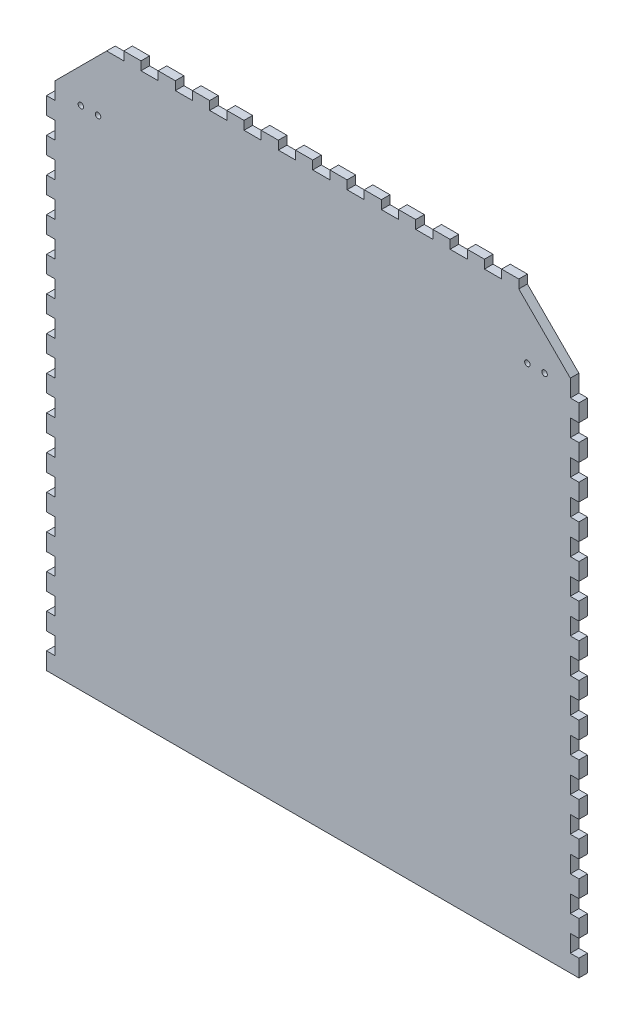
SolidWorks part; units mm, degrees
material "Buche"
ref_plane "Ebene vorne" through (0, 0, 0) normal (0, 0, 1) x (1, 0, 0)
ref_plane "Ebene oben" through (0, 0, 0) normal (0, 1, 0) x (1, 0, 0)
ref_plane "Ebene rechts" through (0, 0, 0) normal (1, 0, 0) x (0, 0, -1)
sketch "Skizze1" plane through (0, 0, 0) normal (0, 0, 1) x (1, 0, 0)
  line L0 (5, 10) -> (5, 20)
  line L1 (5, -10) -> (5, 0)
  line L2 (305, 10) -> (305, 20)
  line L3 (55, 250) -> (65, 250)
  line L4 (5, 220) -> (35, 250)
  line L5 (305, 220) -> (275, 250)
  line L6 (35, 250) -> (45, 250)
  line L7 (45, 250) -> (45, 255)
  line L8 (45, 255) -> (55, 255)
  line L9 (55, 255) -> (55, 250)
  line L10 (65, 250) -> (65, 255)
  line L11 (65, 255) -> (75, 255)
  line L12 (75, 255) -> (75, 250)
  line L13 (305, 0) -> (310, 0)
  line L14 (310, 0) -> (310, 10)
  line L15 (310, 10) -> (305, 10)
  line L16 (305, 30) -> (305, 40)
  line L17 (305, 20) -> (310, 20)
  line L18 (310, 20) -> (310, 30)
  line L19 (310, 30) -> (305, 30)
  line L20 (305, 50) -> (305, 60)
  line L21 (305, 40) -> (310, 40)
  line L22 (310, 40) -> (310, 50)
  line L23 (310, 50) -> (305, 50)
  line L24 (305, 70) -> (305, 80)
  line L25 (305, 60) -> (310, 60)
  line L26 (310, 60) -> (310, 70)
  line L27 (310, 70) -> (305, 70)
  line L28 (305, 90) -> (305, 100)
  line L29 (305, 80) -> (310, 80)
  line L30 (310, 80) -> (310, 90)
  line L31 (310, 90) -> (305, 90)
  line L32 (305, 110) -> (305, 120)
  line L33 (305, 100) -> (310, 100)
  line L34 (310, 100) -> (310, 110)
  line L35 (310, 110) -> (305, 110)
  line L36 (305, 130) -> (305, 140)
  line L37 (305, 120) -> (310, 120)
  line L38 (310, 120) -> (310, 130)
  line L39 (310, 130) -> (305, 130)
  line L40 (305, 150) -> (305, 160)
  line L41 (305, 140) -> (310, 140)
  line L42 (310, 140) -> (310, 150)
  line L43 (310, 150) -> (305, 150)
  line L44 (305, 170) -> (305, 180)
  line L45 (305, 160) -> (310, 160)
  line L46 (310, 160) -> (310, 170)
  line L47 (310, 170) -> (305, 170)
  line L48 (305, 190) -> (305, 200)
  line L49 (305, 180) -> (310, 180)
  line L50 (310, 180) -> (310, 190)
  line L51 (310, 190) -> (305, 190)
  line L52 (305, 210) -> (305, 220)
  line L53 (305, 200) -> (310, 200)
  line L54 (310, 200) -> (310, 210)
  line L55 (310, 210) -> (305, 210)
  line L56 (5, 0) -> (0, 0)
  line L57 (0, 0) -> (0, 10)
  line L58 (0, 10) -> (5, 10)
  line L59 (5, 30) -> (5, 40)
  line L60 (0, 20) -> (0, 30)
  line L61 (0, 30) -> (5, 30)
  line L62 (5, 50) -> (5, 60)
  line L63 (0, 40) -> (0, 50)
  line L64 (0, 50) -> (5, 50)
  line L65 (5, 70) -> (5, 80)
  line L66 (0, 60) -> (0, 70)
  line L67 (0, 70) -> (5, 70)
  line L68 (5, 90) -> (5, 100)
  line L69 (0, 80) -> (0, 90)
  line L70 (0, 90) -> (5, 90)
  line L71 (5, 110) -> (5, 120)
  line L72 (0, 100) -> (0, 110)
  line L73 (0, 110) -> (5, 110)
  line L74 (5, 130) -> (5, 140)
  line L75 (0, 120) -> (0, 130)
  line L76 (0, 130) -> (5, 130)
  line L77 (5, 150) -> (5, 160)
  line L78 (0, 140) -> (0, 150)
  line L79 (0, 150) -> (5, 150)
  line L80 (5, 170) -> (5, 180)
  line L81 (0, 160) -> (0, 170)
  line L82 (0, 170) -> (5, 170)
  line L83 (5, 190) -> (5, 200)
  line L84 (0, 180) -> (0, 190)
  line L85 (0, 190) -> (5, 190)
  line L86 (5, 210) -> (5, 220)
  line L87 (0, 200) -> (0, 210)
  line L88 (0, 210) -> (5, 210)
  line L89 (0, 20) -> (5, 20)
  line L90 (0, 40) -> (5, 40)
  line L91 (0, 60) -> (5, 60)
  line L92 (0, 80) -> (5, 80)
  line L93 (0, 100) -> (5, 100)
  line L94 (0, 120) -> (5, 120)
  line L95 (0, 140) -> (5, 140)
  line L96 (0, 160) -> (5, 160)
  line L97 (0, 180) -> (5, 180)
  line L98 (0, 200) -> (5, 200)
  line L99 (75, 250) -> (85, 250)
  line L100 (85, 250) -> (85, 255)
  line L101 (85, 255) -> (95, 255)
  line L102 (95, 255) -> (95, 250)
  line L103 (95, 250) -> (105, 250)
  line L104 (105, 250) -> (105, 255)
  line L105 (105, 255) -> (115, 255)
  line L106 (115, 255) -> (115, 250)
  line L107 (115, 250) -> (125, 250)
  line L108 (125, 250) -> (125, 255)
  line L109 (125, 255) -> (135, 255)
  line L110 (135, 255) -> (135, 250)
  line L111 (135, 250) -> (145, 250)
  line L112 (145, 250) -> (145, 255)
  line L113 (145, 255) -> (155, 255)
  line L114 (155, 255) -> (155, 250)
  line L115 (155, 250) -> (165, 250)
  line L116 (165, 250) -> (165, 255)
  line L117 (165, 255) -> (175, 255)
  line L118 (175, 255) -> (175, 250)
  line L119 (175, 250) -> (185, 250)
  line L120 (185, 250) -> (185, 255)
  line L121 (185, 255) -> (195, 255)
  line L122 (195, 255) -> (195, 250)
  line L123 (195, 250) -> (205, 250)
  line L124 (205, 250) -> (205, 255)
  line L125 (205, 255) -> (215, 255)
  line L126 (215, 255) -> (215, 250)
  line L127 (215, 250) -> (225, 250)
  line L128 (225, 250) -> (225, 255)
  line L129 (225, 255) -> (235, 255)
  line L130 (235, 255) -> (235, 250)
  line L131 (235, 250) -> (245, 250)
  line L132 (245, 250) -> (245, 255)
  line L133 (245, 255) -> (255, 255)
  line L134 (255, 255) -> (255, 250)
  line L135 (255, 250) -> (265, 250)
  line L136 (265, 250) -> (265, 255)
  line L137 (265, 255) -> (275, 255)
  line L138 (275, 255) -> (275, 250)
  line L139 (5, -20) -> (0, -20)
  line L140 (5, -80) -> (305, -80)
  line L141 (305, -10) -> (305, 0)
  line L142 (0, -20) -> (0, -10)
  line L143 (0, -10) -> (5, -10)
  line L144 (5, -30) -> (5, -20)
  line L145 (5, -40) -> (0, -40)
  line L146 (0, -40) -> (0, -30)
  line L147 (0, -30) -> (5, -30)
  line L148 (5, -50) -> (5, -40)
  line L149 (5, -60) -> (0, -60)
  line L150 (0, -60) -> (0, -50)
  line L151 (0, -50) -> (5, -50)
  line L152 (5, -70) -> (5, -60)
  line L153 (5, -80) -> (0, -80)
  line L154 (0, -80) -> (0, -70)
  line L155 (0, -70) -> (5, -70)
  line L156 (305, -20) -> (310, -20)
  line L157 (310, -20) -> (310, -10)
  line L158 (310, -10) -> (305, -10)
  line L159 (305, -30) -> (305, -20)
  line L160 (305, -40) -> (310, -40)
  line L161 (310, -40) -> (310, -30)
  line L162 (310, -30) -> (305, -30)
  line L163 (305, -50) -> (305, -40)
  line L164 (305, -60) -> (310, -60)
  line L165 (310, -60) -> (310, -50)
  line L166 (310, -50) -> (305, -50)
  line L167 (305, -70) -> (305, -60)
  line L168 (305, -80) -> (310, -80)
  line L169 (310, -80) -> (310, -70)
  line L170 (310, -70) -> (305, -70)
  circle A0 centre (20, 215) radius 1.6
  circle A1 centre (30, 215) radius 1.6
  circle A2 centre (290, 215) radius 1.6
  circle A3 centre (280, 215) radius 1.6
  dimension "D2" = 5
  dimension "D1" = 12
  dimension "D3" = 5
extrude "Aufsatz-Linear austragen1" add sketch "Skizze1" along normal blind 5
